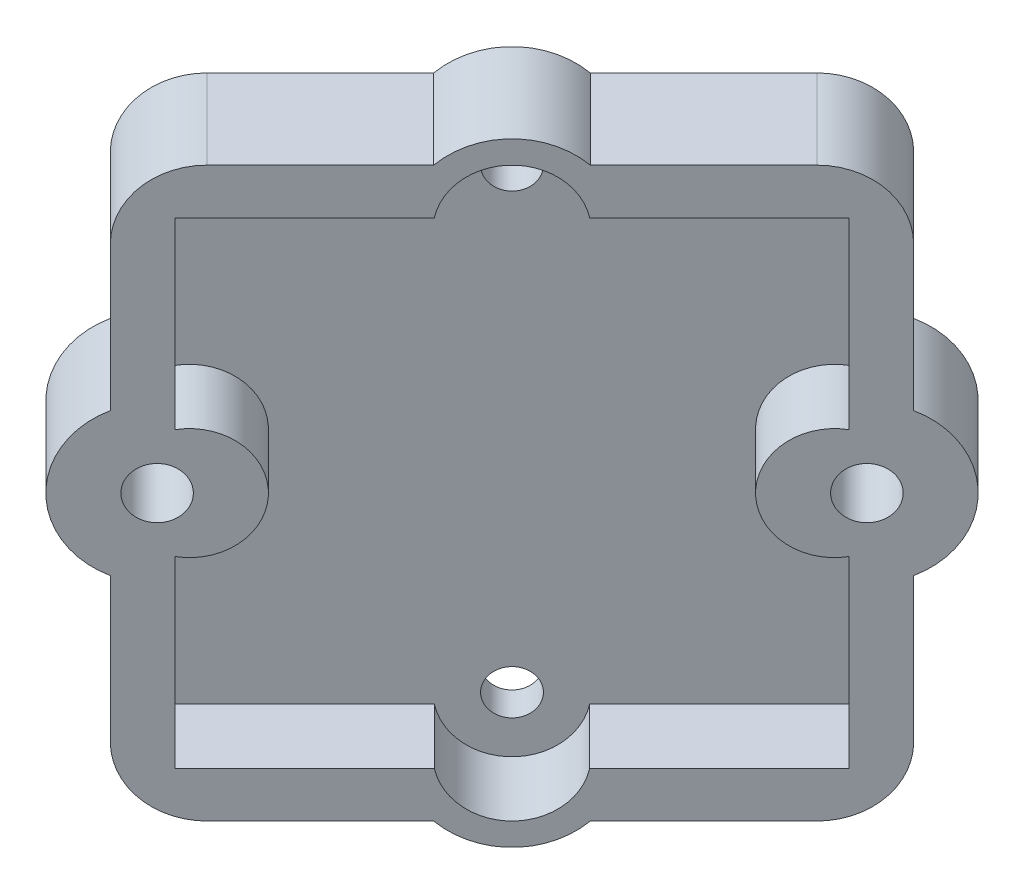
SolidWorks part; units mm, degrees
ref_plane "Front Plane" through (0, 0, 0) normal (0, 0, 1) x (1, 0, 0)
ref_plane "Top Plane" through (0, 0, 0) normal (0, 1, 0) x (1, 0, 0)
ref_plane "Right Plane" through (0, 0, 0) normal (1, 0, 0) x (0, 0, -1)
sketch "Sketch1" plane through (69.3942, 0, 69.3942) normal (0.7071, 0, 0.7071) x (0.7071, 0, -0.7071)
  line L0 (35.9518, 27.5) -> (35.9518, 4) construction
  line L1 (21.4968, 27.5) -> (50.4068, 27.5) construction
  line L2 (14.6218, 4) -> (57.2818, 4) construction
  line L3 (24.9518, 17.5) -> (46.9518, 17.5) construction
  line L9 (35.9518, 27.5) -> (35.9518, 7.05) construction
  line L10 (25.5018, 17.5) -> (46.4018, 17.5) construction
  line L14 (23.5018, 8.05) -> (23.5018, 14.3695)
  line L15 (26.5018, 29.95) -> (33.5228, 29.95)
  line L16 (48.4018, 8.05) -> (48.4018, 14.3695)
  line L17 (26.5018, 5.05) -> (33.5228, 5.05)
  line L18 (23.5018, 20.6305) -> (23.5018, 26.95)
  line L19 (48.4018, 20.6305) -> (48.4018, 26.95)
  line L20 (38.3808, 29.95) -> (45.4018, 29.95)
  line L25 (35.9518, 27.5) -> (35.9518, 7.5) construction
  line L26 (25.9533, 17.5) -> (45.9503, 17.5) construction
  line L27 (38.3808, 5.05) -> (45.4018, 5.05)
  line L28 (57.2818, 4) -> (57.2818, 13.728) construction
  arc A0 (23.5018, 20.6305) -> (23.5018, 14.3695) centre (24.9518, 17.5) ccw
  arc A2 (48.4018, 20.6305) -> (48.4018, 14.3695) centre (46.9518, 17.5) cw
  arc A4 (23.5018, 8.05) -> (26.5018, 5.05) centre (26.5018, 8.05) ccw
  arc A5 (48.4018, 8.05) -> (45.4018, 5.05) centre (45.4018, 8.05) cw
  arc A6 (45.4018, 29.95) -> (48.4018, 26.95) centre (45.4018, 26.95) cw
  arc A7 (23.5018, 26.95) -> (26.5018, 29.95) centre (26.5018, 26.95) cw
  arc A10 (38.3808, 29.95) -> (33.5228, 29.95) centre (35.9518, 27.5) ccw
  arc A11 (38.3808, 5.05) -> (33.5228, 5.05) centre (35.9518, 7.5) cw
  point P10 (35.9518, 17.5)
  point P27 (35.9518, 17.5)
  dimension "D1" = 3
  dimension "D2" = 3.45
  dimension "D3" = 8.88
  dimension "D4" = 18.901
extrude "Boss-Extrude1" add sketch "Sketch1" along normal blind 4.95
sketch "Sketch2" plane through (72.8944, 0, 72.8944) normal (0.7071, 0, 0.7071) x (0.7071, 0, -0.7071)
  line L0 (38.3601, 27.95) -> (46.4018, 27.95)
  line L2 (25.5018, 7.05) -> (33.5435, 7.05)
  line L4 (48.4018, 8.05) -> (48.4018, 14.3695) construction
  line L6 (38.3808, 5.05) -> (45.4018, 5.05) construction
  line L8 (25.5018, 7.05) -> (25.5018, 15.0917)
  line L18 (35.9518, 29.9789) -> (35.9518, 29.95) construction
  line L19 (25.5018, 27.95) -> (33.5435, 27.95)
  line L25 (46.4018, 7.05) -> (46.4018, 15.0917)
  line L26 (35.9518, 27.95) -> (35.9518, 7.05) construction
  line L37 (25.5018, 17.5) -> (46.4018, 17.5) construction
  line L38 (38.3601, 7.05) -> (46.4018, 7.05)
  line L40 (25.5018, 19.9083) -> (25.5018, 27.95)
  line L41 (46.4018, 19.9083) -> (46.4018, 27.95)
  arc A19 (38.3601, 27.95) -> (33.5435, 27.95) centre (35.9518, 27.5) ccw
  arc A21 (25.5018, 15.0917) -> (25.5018, 19.9083) centre (25.9518, 17.5) ccw
  arc A22 (46.4018, 19.9083) -> (46.4018, 15.0917) centre (45.9518, 17.5) ccw
  arc A25 (33.5435, 7.05) -> (38.3601, 7.05) centre (35.9518, 7.5) ccw
  point P6 (35.9518, 17.5)
  point P7 (35.9518, 19.9083)
  point P39 (35.9518, 17.5)
  dimension "D4" = 2.45
  dimension "D5" = 10.0417
  dimension "D2" = 2.45
  dimension "D8" = 2
  dimension "D10" = 10.0417
extrude "Cut-Extrude1" cut sketch "Sketch2" against normal blind 3.45
sketch "Sketch3" plane through (70.4549, 0, 70.4549) normal (0.7071, 0, 0.7071) x (0.7071, 0, -0.7071)
  line L0 (35.9518, 27.5) -> (35.9518, 7.5) construction
  circle A0 centre (35.9518, 27.5) radius 0.975
  circle A1 centre (35.9518, 7.5) radius 0.975
extrude "Cut-Extrude2" cut sketch "Sketch3" against normal up to next
sketch "Sketch4" plane through (72.8944, 0, 72.8944) normal (0.7071, 0, 0.7071) x (0.7071, 0, -0.7071)
  line L0 (24.9518, 17.5) -> (46.9518, 17.5) construction
  circle A0 centre (24.9518, 17.5) radius 1.125
  circle A1 centre (46.9518, 17.5) radius 1.125
  dimension "D2" = 2.25
  dimension "D1" = 22
extrude "Cut-Extrude3" cut sketch "Sketch4" against normal up to next
